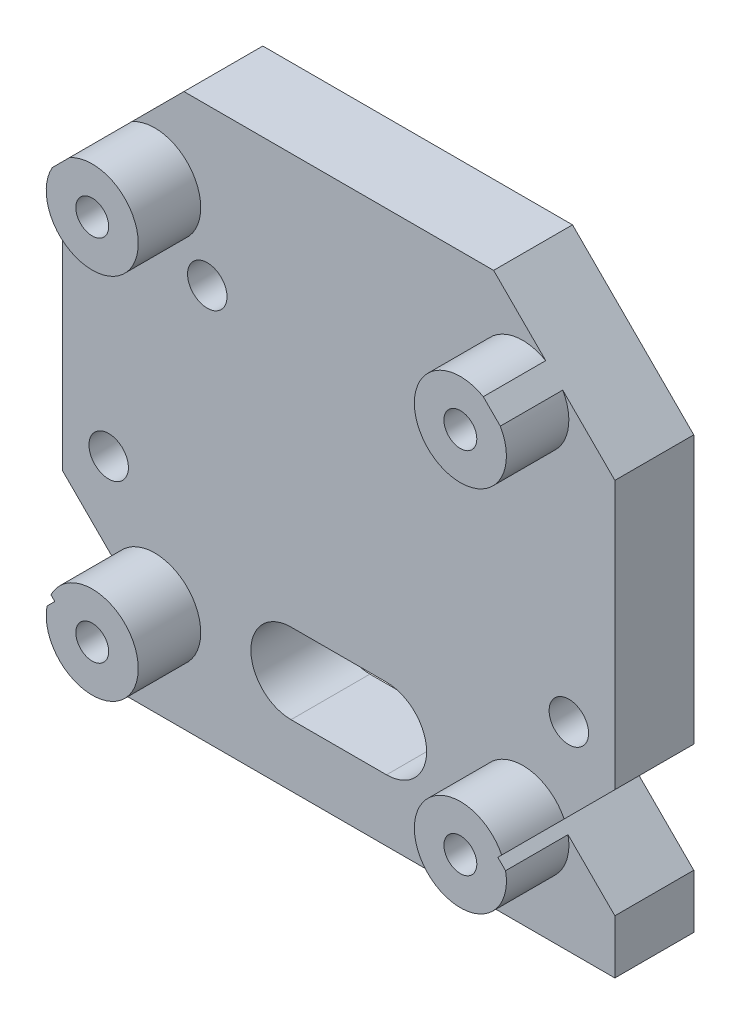
SolidWorks part; units mm, degrees
ref_plane "Front Plane" through (0, 0, 0) normal (0, 0, 1) x (1, 0, 0)
ref_plane "Top Plane" through (0, 0, 0) normal (0, 1, 0) x (1, 0, 0)
ref_plane "Right Plane" through (0, 0, 0) normal (1, 0, 0) x (0, 0, -1)
sketch "Sketch1" plane through (0, 0, 0) normal (0, 0, 1) x (1, 0, 0)
  line L1 (-14, -14) -> (14, -14) construction
  line L2 (-14, -14) -> (-14, 14) construction
  line L3 (-14, 14) -> (14, 14) construction
  line L4 (14, -14) -> (14, 14) construction
  line L5 (-14, -14) -> (14, 14) construction
  line L6 (-14, 14) -> (14, -14) construction
  line L7 (-21, -21) -> (21, -21)
  line L8 (-21, -21) -> (-21, 21)
  line L9 (-21, 21) -> (21, 21)
  line L10 (21, -21) -> (21, 21)
  line L11 (-21, -21) -> (21, 21) construction
  line L12 (-21, 21) -> (21, -21) construction
  circle A0 centre (-14, 14) radius 1.25
  circle A1 centre (14, 14) radius 1.25
  circle A2 centre (14, -14) radius 1.25
  circle A3 centre (-14, -14) radius 1.25
  point P0 (0, 0)
  point P10 (0, 0)
  dimension "D2" = 2.5
  dimension "D1" = 28
  dimension "D3" = 42
extrude "Boss-Extrude1" add sketch "Sketch1" against normal blind 6
sketch "Sketch2" plane through (0, 0, 0) normal (0, 0, 1) x (1, 0, 0)
  line L0 (-3.6316, -13.2494) -> (3.6312, -13.2494) construction
  line L1 (-3.6316, -10.1988) -> (3.6312, -10.1988)
  line L2 (-3.6316, -16.3) -> (3.6312, -16.3)
  arc A0 (-3.6316, -10.1988) -> (-3.6316, -16.3) centre (-3.6316, -13.2494) ccw
  arc A1 (3.6312, -16.3) -> (3.6312, -10.1988) centre (3.6312, -13.2494) ccw
  point P2 (-0.0002, -13.2494)
extrude "Cut-Extrude1" cut sketch "Sketch2" against normal through all
sketch "Sketch3" plane through (0, 0, 0) normal (0, 0, 1) x (1, 0, 0)
  circle A0 centre (-14, 14) radius 3.5
  circle A1 centre (14, 14) radius 3.5
  circle A2 centre (-14, -14) radius 3.5
  circle A3 centre (14, -14) radius 3.5
  circle A4 centre (-14, 14) radius 1.25
  circle A5 centre (-14, 14) radius 1.25 construction
  circle A6 centre (14, 14) radius 1.25
  circle A7 centre (14, -14) radius 1.25
  circle A8 centre (-14, -14) radius 1.25
  dimension "D1" = 7
extrude "Boss-Extrude2" add sketch "Sketch3" along normal blind 4.75
sketch "Sketch4" plane through (0, 0, 0) normal (0, 0, 1) x (1, 0, 0)
  line L0 (-21.6611, -7.937) -> (-16.8481, -12.75)
  line L1 (-16.8481, -12.75) -> (-21.6611, -17.563)
  line L2 (-21.6611, -17.563) -> (-21.6611, -7.937)
  line L3 (0, -9.2674) -> (0, 0) construction
  line L4 (-21.7053, 11.0724) -> (-11.3059, 21.4718)
  line L5 (-11.3059, 21.4718) -> (-21.7053, 21.4718)
  line L6 (-21.7053, 21.4718) -> (-21.7053, 11.0724)
  line L7 (-10, 9.1173) -> (-17.5, -5.8827) construction
  line L8 (-17.5, -5.8827) -> (-10, -5.8827) construction
  line L9 (-10, -5.8827) -> (-10, 9.1173) construction
  circle A0 centre (-17.5, -5.8827) radius 1.5
  circle A1 centre (-10, 9.1173) radius 1.5
  point P11 (0, 0)
  dimension "D2" = 3
  dimension "D1" = 45
  dimension "D3" = 16.7705
  dimension "D4" = 15
  dimension "D5" = 10
extrude "Cut-Extrude2" cut sketch "Sketch4" against normal through all both and the other way through all
mirror "Mirror1" about plane through (0, 0, 0) normal (1, 0, 0) of "Cut-Extrude2"
sketch "Sketch5" plane through (0, 0, -6) normal (0, 0, -1) x (-1, 0, 0)
  line L0 (-11.7777, 21) -> (-21, 11.7777) construction
  line L1 (-13.223, 11.1001) -> (-11.1001, 13.223)
  line L2 (-11.1001, 13.223) -> (-11.8771, 16.1229)
  line L3 (-11.8771, 16.1229) -> (-14.777, 16.8999)
  line L4 (-14.777, 16.8999) -> (-16.8999, 14.777)
  line L5 (-16.8999, 14.777) -> (-16.1229, 11.8771)
  line L6 (-16.1229, 11.8771) -> (-13.223, 11.1001)
  line L13 (21, -21) -> (-21, -21) construction
  line L14 (13.223, 11.1001) -> (16.1229, 11.8771)
  line L15 (16.1229, 11.8771) -> (16.8999, 14.777)
  line L16 (16.8999, 14.777) -> (14.777, 16.8999)
  line L17 (14.777, 16.8999) -> (11.8771, 16.1229)
  line L18 (11.8771, 16.1229) -> (11.1001, 13.223)
  line L19 (11.1001, 13.223) -> (13.223, 11.1001)
  line L20 (15.5011, -16.6) -> (17.0022, -14)
  line L21 (17.0022, -14) -> (15.5011, -11.4)
  line L22 (15.5011, -11.4) -> (12.4989, -11.4)
  line L23 (12.4989, -11.4) -> (10.9978, -14)
  line L24 (10.9978, -14) -> (12.4989, -16.6)
  line L25 (12.4989, -16.6) -> (15.5011, -16.6)
  line L26 (-15.5011, -16.6) -> (-12.4989, -16.6)
  line L27 (-12.4989, -16.6) -> (-10.9978, -14)
  line L28 (-10.9978, -14) -> (-12.4989, -11.4)
  line L29 (-12.4989, -11.4) -> (-15.5011, -11.4)
  line L30 (-15.5011, -11.4) -> (-17.0022, -14)
  line L31 (-17.0022, -14) -> (-15.5011, -16.6)
  line L32 (11.7777, 21) -> (21, 11.7777) construction
  circle A0 centre (-14, 14) radius 2.6 construction
  circle A1 centre (-14, 14) radius 1.25 construction
  circle A3 centre (14, 14) radius 2.6 construction
  circle A4 centre (14, 14) radius 1.25 construction
  circle A5 centre (14, -14) radius 2.6 construction
  circle A6 centre (-14, -14) radius 2.6 construction
  circle A7 centre (-14, -14) radius 1.25 construction
  circle A8 centre (14, -14) radius 1.25 construction
  dimension "D1" = 5.2
extrude "Cut-Extrude3" cut sketch "Sketch5" against normal blind 2.3
